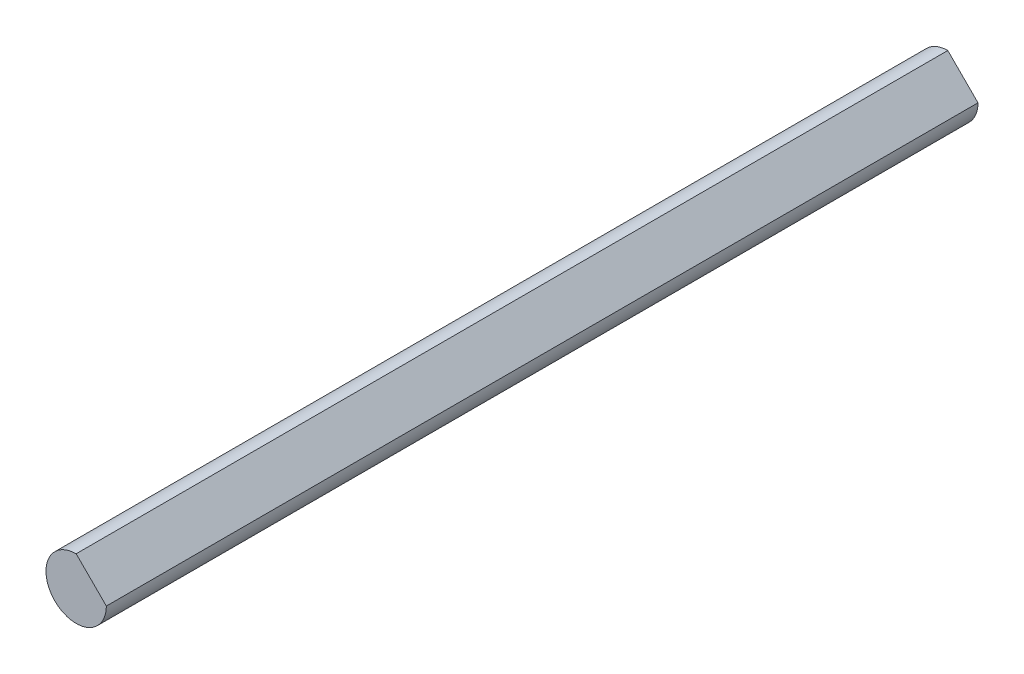
SolidWorks part; units mm, degrees
ref_plane "Front Plane" through (0, 0, 0) normal (0, 0, 1) x (1, 0, 0)
ref_plane "Top Plane" through (0, 0, 0) normal (0, 1, 0) x (1, 0, 0)
ref_plane "Right Plane" through (0, 0, 0) normal (1, 0, 0) x (0, 0, -1)
sketch "Sketch1" plane through (0, 0, 0) normal (0, 0, 1) x (1, 0, 0)
  circle A0 centre (0, 0) radius 3.81
  dimension "D1" = 7.62
extrude "Boss-Extrude1" add sketch "Sketch1" along normal blind 110
sketch "Sketch2" plane through (0, 0, 110) normal (0, 0, 1) x (1, 0, 0)
  line L0 (0, 3.81) -> (3.81, 0)
  circle A0 centre (0, 0) radius 3.81 construction
  circle A1 centre (0, 0) radius 3.81
  circle M2 centre (0, 0) radius 3.81
extrude "Cut-Extrude1" cut sketch "Sketch2" against normal through all contours L0 M2
